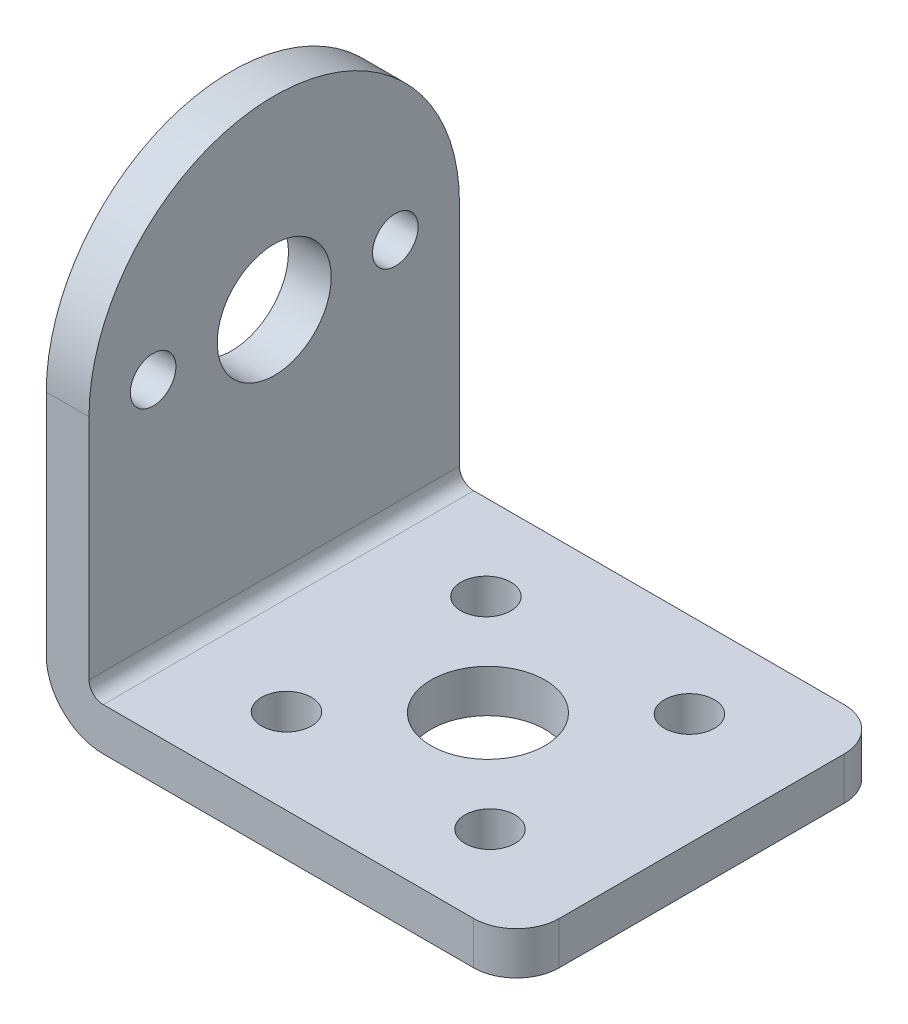
SolidWorks part; units mm, degrees
material "PMMA"
ref_plane "Plan de face" through (0, 0, 0) normal (0, 0, 1) x (1, 0, 0)
ref_plane "Plan de dessus" through (0, 0, 0) normal (0, 1, 0) x (1, 0, 0)
ref_plane "Plan de droite" through (0, 0, 0) normal (1, 0, 0) x (0, 0, -1)
sketch "Esquisse1" plane through (0, 0, 0) normal (0, 0, 1) x (1, 0, 0)
  line L0 (0, 4) -> (0, 33)
  line L1 (4, 0) -> (33, 0)
  arc A0 (0, 4) -> (4, 0) centre (4, 4) ccw
  point P6 (0, 0)
  dimension "D3" = 4
  dimension "D1" = 33
  dimension "D2" = 33
extrude "Extru.-Mince1" add sketch "Esquisse1" along normal blind 13 and the other way blind 13 thin
sketch "Esquisse2" plane through (0, 3, 0) normal (0, 1, 0) x (1, 0, 0)
  line L0 (-3.499, 0) -> (34.7753, 0) construction
  line L1 (18, 12.5763) -> (18, -12.5763) construction
  line L2 (10.8586, 7) -> (25.1414, -7) construction
  circle A0 centre (18, 0) radius 4
  circle A1 centre (10.8586, 7) radius 1.75
  circle A2 centre (10.8586, -7) radius 1.75
  circle A3 centre (25.1414, -7) radius 1.75
  circle A4 centre (25.1414, 7) radius 1.75
  point P12 (18, 0)
  dimension "D2" = 8
  dimension "D5" = 3.5
  dimension "D1" = 18
  dimension "D3" = 7
  dimension "D4" = 20
extrude "Enlèv. mat.-Extru.1" cut sketch "Esquisse2" against normal through all
sketch "Esquisse3" plane through (3, 0, 0) normal (1, 0, 0) x (0, 0, -1)
  line L0 (0, -1.7328) -> (0, 34.4597) construction
  line L3 (13, 20) -> (15, 20)
  line L4 (-15, 20) -> (-13, 20)
  line L5 (-15, 20) -> (-15, 35)
  line L6 (-15, 35) -> (15, 35)
  line L7 (15, 20) -> (15, 35)
  line L8 (-19.323, 20) -> (19.2913, 20) construction
  arc A0 (13, 20) -> (-13, 20) centre (0, 20) ccw
  circle A1 centre (0, 20) radius 4
  circle A2 centre (-8.5, 20) radius 1.6
  circle A3 centre (8.5, 20) radius 1.6
  dimension "D1" = 20
  dimension "D4" = 13
  dimension "D5" = 20
  dimension "D6" = 8
  dimension "D8" = 3.2
  dimension "D2" = 15
  dimension "D3" = 30
  dimension "D7" = 8.5
extrude "Enlèv. mat.-Extru.2" cut sketch "Esquisse3" against normal through all
chamfer "Chanfrein1" distance 0.5 angle 45 2 edges at (0, 20, 6.9) (0, 20, -6.9)
fillet "Congé1" radius 3 2 edges at (33, 1.5, 13) (33, 1.5, -13)
